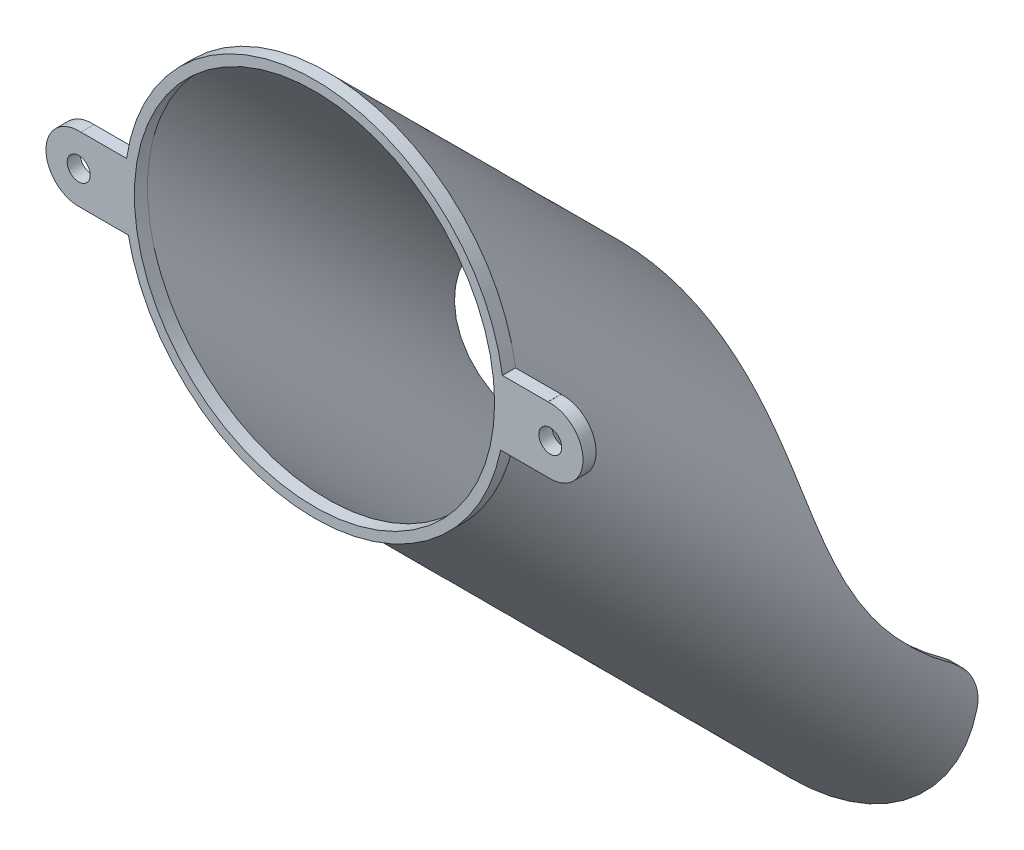
SolidWorks part; units mm, degrees
ref_plane "前基準面" through (0, 0, 0) normal (0, 0, 1) x (1, 0, 0)
ref_plane "上基準面" through (0, 0, 0) normal (0, 1, 0) x (1, 0, 0)
ref_plane "右基準面" through (0, 0, 0) normal (1, 0, 0) x (0, 0, -1)
sketch "草圖1" plane through (0, 0, 0) normal (0, 0, 1) x (1, 0, 0)
  circle A0 centre (0, 0) radius 29
  circle A1 centre (0, 0) radius 27.5
  dimension "D1" = 58
  dimension "D2" = 1.5
sketch "草圖2" plane through (0, 0, 0) normal (1, 0, 0) x (0, 0, -1)
  line L0 (0, 0) -> (70.7107, -70.7107) construction
  line L1 (0, 29) -> (0, -29) construction
  line L2 (0, 0) -> (70.7107, -70.7107)
  dimension "D1" = 135
  dimension "D2" = 100
sweep "掃出1" add profiles "草圖1" path "草圖2"
sketch "草圖3" plane through (0, 0, 0) normal (1, 0, 0) x (0, 0, -1)
  circle A0 centre (98.0275, -24.0292) radius 54.0867
extrude "除料-伸長1" cut sketch "草圖3" against normal through all and the other way through all
sketch "草圖4" plane through (0, 0, 0) normal (0, 0, 1) x (1, 0, 0)
  line L0 (0, 0) -> (0, -0.77) construction
  line L1 (0, -0.77) -> (-56.874, -0.77) construction
  line L2 (-36, 4.23) -> (-28.6898, 4.23)
  line L3 (-36, -5.77) -> (-28.4202, -5.77)
  line L4 (36, 4.23) -> (28.6898, 4.23)
  line L5 (36, -5.77) -> (28.4202, -5.77)
  circle A0 centre (0, -0.77) radius 36
  circle A1 centre (-36, -0.77) radius 5
  circle A2 centre (-36, -0.77) radius 1.75
  circle A3 centre (0, 0) radius 29 construction
  arc A4 (-28.6898, 4.23) -> (-28.4202, -5.77) centre (0, 0) ccw
  arc A5 (28.6898, 4.23) -> (28.4202, -5.77) centre (0, 0) cw
  circle A6 centre (36, -0.77) radius 1.75
  circle A7 centre (36, -0.77) radius 5
  circle A8 centre (0, 0) radius 27.5
  circle A9 centre (0, 0) radius 29
  dimension "D2" = 72
  dimension "D3" = 3.5
  dimension "D4" = 10
  dimension "D1" = 1.54
extrude "填料-伸長2" add sketch "草圖4" along normal blind 2 contours A2 A0 A1 | A2 A0 A1 | A4 L2 A0 A1 L3 | A5 A9 A4 A8 | A0 A7 L4 A5 L5 | A7 A0 A6 | A7 A0 A6
fillet "圓角1" radius 10 2 edges at (-28.25, -70.7107, -70.7107) (28.25, -70.7107, -70.7107)
